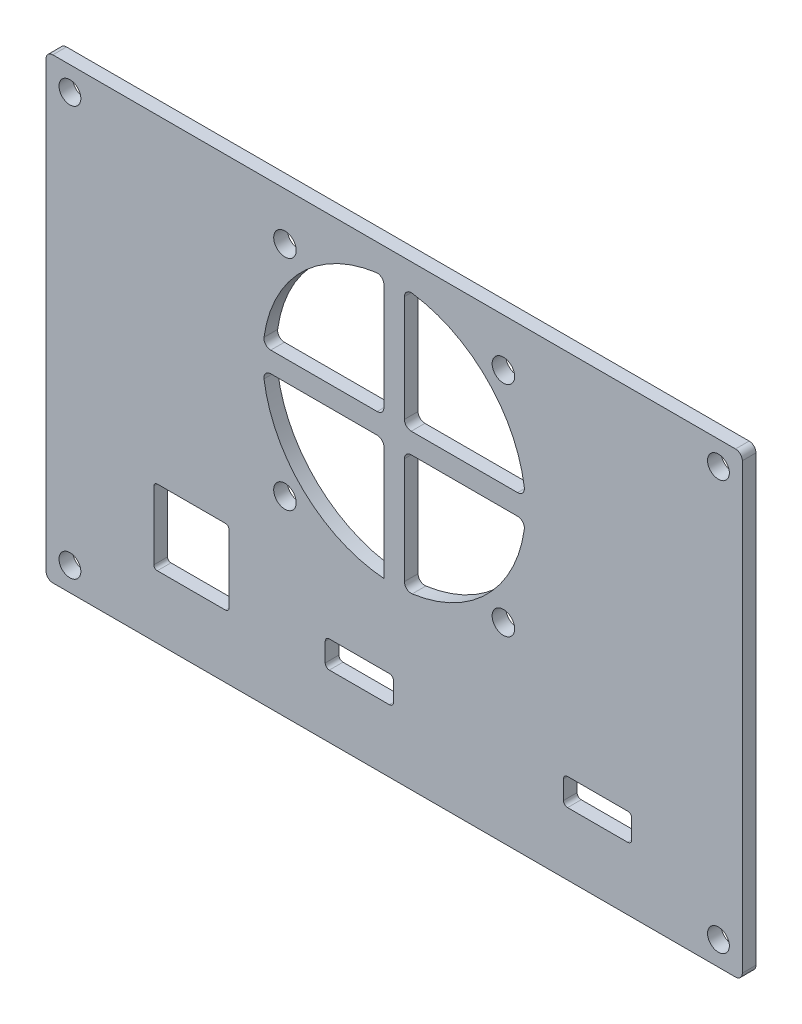
SolidWorks part; units mm, degrees
ref_plane "前视基准面" through (0, 0, 0) normal (0, 0, 1) x (1, 0, 0)
ref_plane "上视基准面" through (0, 0, 0) normal (0, 1, 0) x (1, 0, 0)
ref_plane "右视基准面" through (0, 0, 0) normal (1, 0, 0) x (0, 0, -1)
other "Configuration Table"
sketch "草图1" plane through (0, 0, 0) normal (0, 0, 1) x (1, 0, 0)
  line L1 (0, 0) -> (102, 0)
  line L2 (0, 0) -> (0, 67)
  line L3 (0, 67) -> (102, 67)
  line L4 (102, 0) -> (102, 67)
  dimension "D1" = 102
  dimension "D2" = 67
extrude "凸台-拉伸1" add sketch "草图1" along normal blind 2
sketch "草图2" plane through (0, 0, 2) normal (0, 0, 1) x (1, 0, 0)
  line L0 (102, 67) -> (0, 67) construction
  line L1 (0, 67) -> (0, 0) construction
  line L2 (102, 0) -> (102, 67) construction
  line L3 (0, 0) -> (102, 0) construction
  circle A0 centre (3.5, 63.5) radius 1.6
  circle A2 centre (98.5, 63.5) radius 1.6
  circle A3 centre (98.5, 3.5) radius 1.6
  circle A4 centre (3.5, 3.5) radius 1.6
  point P18 (2.638, -0.9395)
  dimension "D1" = 3.2
  dimension "D2" = 3.5
  dimension "D3" = 3.5
  dimension "D4" = 3.5
  dimension "D5" = 3.5
  dimension "D6" = 3.5
  dimension "D7" = 3.5
extrude "切除-拉伸1" cut sketch "草图2" against normal through all
fillet "圆角1" radius 1 4 edges at (102, 67, 1) (102, 0, 1) (0, 0, 1) (0, 67, 1)
sketch "草图3" plane through (0, 0, 2) normal (0, 0, 1) x (1, 0, 0)
  line L0 (1, 0) -> (101, 0) construction
  line L1 (75.8, 13.15) -> (85.8, 13.15)
  line L2 (75.8, 13.15) -> (75.8, 9.2)
  line L3 (75.8, 9.2) -> (85.8, 9.2)
  line L4 (85.8, 13.15) -> (85.8, 9.2)
  line L5 (102, 1) -> (102, 66) construction
  line L6 (40.9, 13.15) -> (50.9, 13.15)
  line L7 (40.9, 13.15) -> (40.9, 9.2)
  line L8 (40.9, 9.2) -> (50.9, 9.2)
  line L9 (50.9, 13.15) -> (50.9, 9.2)
  line L10 (0, 66) -> (0, 1) construction
  line L11 (26.8, 9.2) -> (15.8, 9.2)
  line L12 (26.8, 9.2) -> (26.8, 20.2)
  line L13 (26.8, 20.2) -> (15.8, 20.2)
  line L14 (15.8, 9.2) -> (15.8, 20.2)
  line L15 (101, 67) -> (1, 67) construction
  line L16 (52.5, 42.5) -> (70.1915, 42.5)
  line L17 (31.8085, 45.5) -> (49.5, 45.5)
  line L19 (31.8085, 42.5) -> (49.5, 42.5)
  line L22 (49.5, 63.1915) -> (49.5, 45.5)
  line L24 (52.5, 63.1915) -> (52.5, 45.5)
  line L25 (52.5, 42.5) -> (52.5, 24.8085)
  line L26 (52.5, 45.5) -> (70.1915, 45.5)
  line L27 (49.5, 42.5) -> (49.5, 24.8085)
  arc A0 (70.1915, 45.5) -> (52.5, 63.1915) centre (51, 44) ccw
  circle A1 centre (35, 60) radius 1.65
  circle A2 centre (67, 60) radius 1.65
  circle A3 centre (67, 28) radius 1.65
  circle A4 centre (35, 28) radius 1.65
  arc A5 (31.8085, 42.5) -> (49.5, 24.8085) centre (51, 44) ccw
  arc A6 (52.5, 24.8085) -> (70.1915, 42.5) centre (51, 44) ccw
  arc A7 (49.5, 63.1915) -> (31.8085, 45.5) centre (51, 44) ccw
  point P32 (0, 0)
  dimension "D10" = 38.5
  dimension "D11" = 3.3
  dimension "D18" = 1.5
  dimension "D1" = 9.2
  dimension "D2" = 3.95
  dimension "D3" = 10
  dimension "D4" = 16.2
  dimension "D5" = 51.1
  dimension "D6" = 10
  dimension "D7" = 15.8
  dimension "D8" = 11
  dimension "D9" = 11
  dimension "D12" = 16
  dimension "D13" = 16
  dimension "D14" = 16
  dimension "D15" = 32
  dimension "D16" = 51
  dimension "D17" = 23
  dimension "D20" = 1.5
extrude "切除-拉伸2" cut sketch "草图3" against normal through all
fillet "圆角2" radius 1 11 edges at (52.5, 63.1915, 1) (49.5, 63.1915, 1) (31.8085, 45.5, 1) (31.8085, 42.5, 1) (52.5, 24.8085, 1) (70.1915, 42.5, 1) (70.1915, 45.5, 1) (49.5, 45.5, 1) (52.5, 45.5, 1) (52.5, 42.5, 1) (49.5, 42.5, 1)
fillet "圆角3" radius 0.6 8 edges at (40.9, 9.2, 1) (40.9, 13.15, 1) (50.9, 9.2, 1) (50.9, 13.15, 1) (75.8, 13.15, 1) (75.8, 9.2, 1) (85.8, 9.2, 1) (85.8, 13.15, 1)
fillet "圆角4" radius 0.5 4 edges at (15.8, 9.2, 1) (15.8, 20.2, 1) (26.8, 20.2, 1) (26.8, 9.2, 1)
